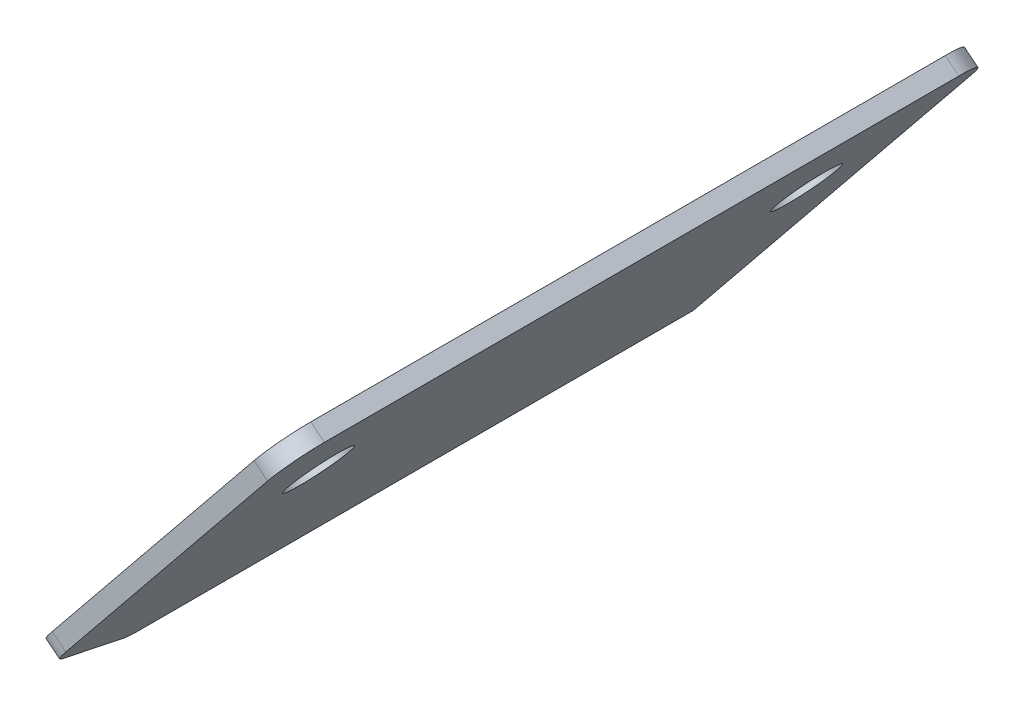
SolidWorks part; units mm, degrees
ref_plane "Front Plane" through (0, 0, 0) normal (0, 0, 1) x (1, 0, 0)
ref_plane "Top Plane" through (0, 0, 0) normal (0, 1, 0) x (1, 0, 0)
ref_plane "Right Plane" through (0, 0, 0) normal (1, 0, 0) x (0, 0, -1)
sketch "Sketch1" plane through (0, 0, 0) normal (0, 0, 1) x (1, 0, 0)
  line L0 (-443.9659, -405.9885) -> (-553.4463, -541.0616)
  line L1 (-117.475, -3.175) -> (-507.9403, -484.9179) construction
  line L2 (-553.4463, -541.0616) -> (-558.3793, -537.0632)
  line L3 (-558.3793, -537.0632) -> (-448.899, -401.9901)
  line L4 (-448.899, -401.9901) -> (-443.9659, -405.9885)
  circle A1 centre (-606.425, -606.425) radius 84.1375 construction
  point P8 (-507.9403, -484.9179)
  dimension "D1" = 6.35
  dimension "D2" = 101.6
extrude "Boss-Extrude1" add sketch "Sketch1" along normal up to surface (256.54 mm away)
sketch "Sketch2" plane through (-74.2782, 60.2044, 0) normal (-0.7769, 0.6297, 0) x (0, 0, 1)
  line L0 (128.27, -594.9492) -> (121.92, -696.5492) construction
  line L1 (256.54, -594.9492) -> (0, -594.9492) construction
  line L2 (243.84, -696.5492) -> (0, -696.5492) construction
  line L3 (213.995, -645.7492) -> (36.195, -645.7492) construction
  circle A0 centre (213.995, -645.7492) radius 11.1125
  circle A1 centre (36.195, -645.7492) radius 11.1125
  point P8 (125.095, -645.7492)
  dimension "D2" = 22.225
  dimension "D1" = 177.8
extrude "Cut-Extrude1" cut sketch "Sketch2" against normal up to next
sketch "Sketch3" plane through (-69.3451, 56.206, 0) normal (0.7769, -0.6297, 0) x (0, 0, -1)
  line L0 (-205.74, -768.8189) -> (-256.54, -730.7189)
  line L1 (-256.54, -768.8189) -> (0, -768.8189) construction
  line L2 (-256.54, -768.8189) -> (-256.54, -594.9492) construction
  dimension "D1" = 50.8
  dimension "D2" = 38.1
extrude "Cut-Extrude2" cut sketch "Sketch3" against normal through all and the other way through all
fillet "Fillet1" radius 12.7 4 edges at (-531.9224, -509.4639, 256.54) (-555.9128, -539.0624, 205.74) (-446.4325, -403.9893, 0) (-446.4325, -403.9893, 256.54)
